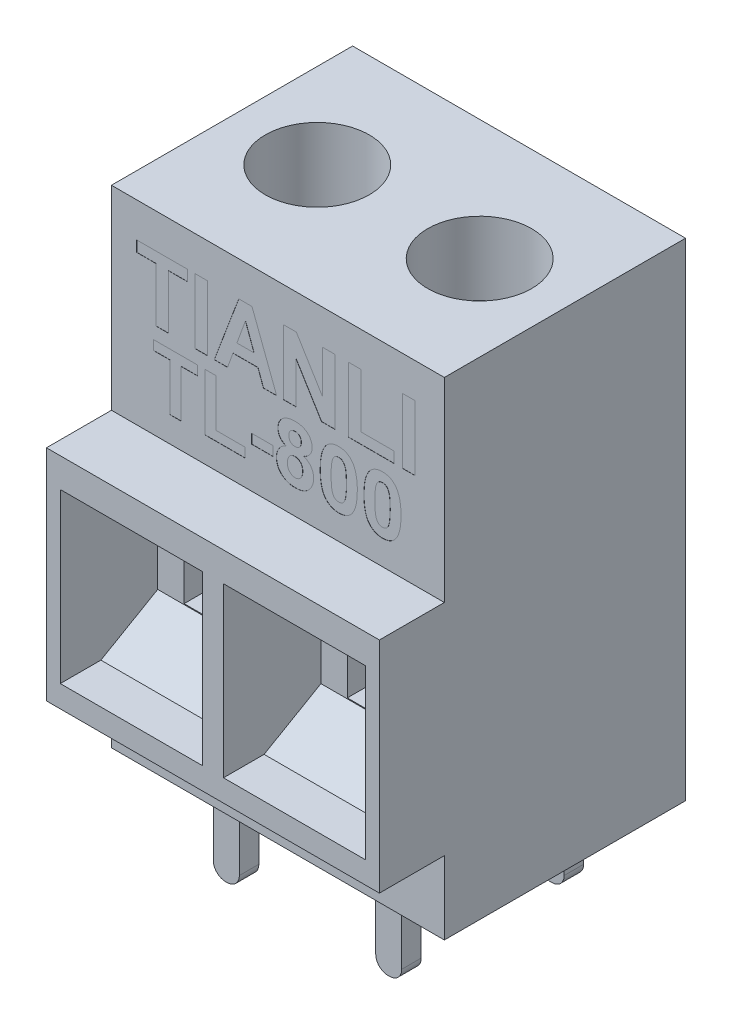
SolidWorks part; units mm, degrees
ref_plane "Front Plane" through (0, 0, 0) normal (0, 0, 1) x (1, 0, 0)
ref_plane "Top Plane" through (0, 0, 0) normal (0, 1, 0) x (1, 0, 0)
ref_plane "Right Plane" through (0, 0, 0) normal (1, 0, 0) x (0, 0, -1)
sketch "Sketch1" plane through (0, 0, 0) normal (1, 0, 0) x (0, 0, -1)
  line L0 (0, 66.3882) -> (0, -65.5147) construction
  line L1 (7.425, 15) -> (-7.425, 15)
  line L2 (-7.425, 15) -> (-7.425, 3)
  line L3 (-7.425, 3) -> (-11.425, 3)
  line L4 (-11.425, 3) -> (-11.425, -10.5)
  line L5 (-11.425, -10.5) -> (-7.425, -10.5)
  line L6 (-7.425, -10.5) -> (-7.425, -15)
  line L7 (-7.425, -15) -> (7.425, -15)
  line L8 (7.425, -15) -> (7.425, 15)
  point P5 (0, -65.5147)
  point P12 (0, 66.3882)
  point P13 (-6.1478, 3.3163)
  point P14 (-6.9448, -29.5223)
  point P15 (0, 15)
  point P16 (7.425, 0)
  dimension "D1" = 14.85
  dimension "D2" = 30
  dimension "D3" = 12
  dimension "D4" = 4
  dimension "D5" = 4.5
extrude "Boss-Extrude1" add sketch "Sketch1" along normal mid plane 20.5
sketch "Sketch2" plane through (0, 0, 11.425) normal (0, 0, 1) x (1, 0, 0)
  line L0 (0, 6.6704) -> (0, -3.1764) construction
  line L1 (9.4, -9.15) -> (0.65, -9.15)
  line L2 (-9.4, 1.2) -> (-0.65, 1.2)
  line L3 (-9.4, 1.2) -> (-9.4, -9.15)
  line L4 (-9.4, -9.15) -> (-0.65, -9.15)
  line L5 (-0.65, 1.2) -> (-0.65, -9.15)
  line L6 (-9.4, 1.2) -> (-0.65, -9.15) construction
  line L7 (-9.4, -9.15) -> (-0.65, 1.2) construction
  line L8 (0.65, 1.2) -> (0.65, -9.15)
  line L9 (9.4, 1.2) -> (0.65, 1.2)
  line L10 (9.4, 1.2) -> (9.4, -9.15)
  line L11 (10.25, -10.5) -> (-10.25, -10.5) construction
  point P3 (-5.025, -3.975)
  dimension "D1" = 8.75
  dimension "D2" = 10.35
  dimension "D3" = 1.35
  dimension "D4" = 1.3
extrude "Cut-Extrude1" cut sketch "Sketch2" against normal blind 6
sketch "Sketch4" plane through (0, 0, 5.425) normal (0, 0, 1) x (1, 0, 0)
  line L0 (-0.65, -9.15) -> (-0.65, 1.2) construction
  line L1 (-2.275, -0.875) -> (-7.775, -0.875)
  line L2 (-2.275, -0.875) -> (-2.275, -7.075)
  line L3 (-2.275, -7.075) -> (-7.775, -7.075)
  line L4 (-7.775, -0.875) -> (-7.775, -7.075)
  line L5 (-2.275, -0.875) -> (-7.775, -7.075) construction
  line L6 (-2.275, -7.075) -> (-7.775, -0.875) construction
  line L7 (-0.65, 1.2) -> (-9.4, 1.2) construction
  line L8 (0, 0) -> (0, 5.9557) construction
  line L9 (2.275, -7.075) -> (7.775, -7.075)
  line L10 (7.775, -0.875) -> (7.775, -7.075)
  line L11 (2.275, -0.875) -> (7.775, -0.875)
  line L12 (2.275, -0.875) -> (2.275, -7.075)
  point P0 (-5.025, -3.975)
  point P7 (-0.65, -3.975)
  point P10 (-5.025, 1.2)
  dimension "D1" = 6.2
  dimension "D2" = 5.5
extrude "Cut-Extrude2" cut sketch "Sketch4" against normal blind 6
chamfer "Chamfer1" distance 3.5 angle 30 4 edges at (5.025, -9.15, 5.425) (5.025, 1.2, 5.425) (-5.025, 1.2, 5.425) (-5.025, -9.15, 5.425)
sketch "Sketch5" plane through (0, 15, 0) normal (0, 1, 0) x (1, 0, 0)
  line L0 (0, 0) -> (-10.25, 0) construction
  line L1 (0, 0) -> (0, -7.425) construction
  line L2 (-10.25, 7.425) -> (-10.25, -7.425) construction
  line L3 (10.25, -7.425) -> (-10.25, -7.425) construction
  circle A0 centre (-5, 0) radius 3.2
  circle A1 centre (5, 0) radius 3.2
  dimension "D1" = 6.4
  dimension "D2" = 10
extrude "Cut-Extrude3" cut sketch "Sketch5" against normal blind 4.5
sketch "Sketch6" plane through (0, 10.5, 0) normal (0, 1, 0) x (1, 0, 0)
  line L0 (-7.2223, 0) -> (-2.7777, 0)
  line L1 (-5, -1.75) -> (-5, 1.75)
  line L2 (0, 0) -> (0, -2.7983) construction
  line L3 (5, -1.75) -> (5, 1.75)
  line L4 (7.2223, 0) -> (2.7777, 0)
  line L5 (-5, 3.2) -> (-5, -3.2) construction
  circle A2 centre (-5, 0) radius 3.2 construction
  circle A3 centre (-5, 0) radius 3.2 construction
  point P2 (-5, 3.2)
  point P3 (-5, 3.2)
  point P10 (-5, 0)
  dimension "D1" = 3.5
  dimension "D2" = 5
extrude "Cut-Extrude-Thin1" cut sketch "Sketch6" against normal blind 1.5 thin thin type mid plane wall 1
sketch "Sketch7" plane through (0, -15, 0) normal (0, -1, 0) x (1, 0, 0)
  line L0 (0, 14.2864) -> (0, -10.6744) construction
  line L1 (-13.0408, 0) -> (12.0493, 0) construction
  line L2 (-4.2, 4.4) -> (-5.8, 4.4)
  line L3 (4.2, 5.6) -> (5.8, 5.6)
  line L4 (4.2, 5.6) -> (4.2, 4.4)
  line L5 (4.2, 4.4) -> (5.8, 4.4)
  line L6 (5.8, 5.6) -> (5.8, 4.4)
  line L7 (4.2, 5.6) -> (5.8, 4.4) construction
  line L8 (4.2, 4.4) -> (5.8, 5.6) construction
  line L9 (-5.8, 5.6) -> (-5.8, 4.4)
  line L10 (-4.2, 5.6) -> (-5.8, 5.6)
  line L11 (-4.2, 5.6) -> (-4.2, 4.4)
  line L12 (-4.2, -5.6) -> (-4.2, -4.4)
  line L13 (-4.2, -5.6) -> (-5.8, -5.6)
  line L14 (-5.8, -5.6) -> (-5.8, -4.4)
  line L15 (-4.2, -4.4) -> (-5.8, -4.4)
  line L16 (4.2, -4.4) -> (5.8, -4.4)
  line L17 (5.8, -5.6) -> (5.8, -4.4)
  line L18 (4.2, -5.6) -> (5.8, -5.6)
  line L19 (4.2, -5.6) -> (4.2, -4.4)
  point P9 (5, 5)
  dimension "D1" = 10
  dimension "D2" = 10
  dimension "D3" = 1.6
  dimension "D4" = 1.2
extrude "Boss-Extrude2" add sketch "Sketch7" along normal blind 5.45
fillet "Fillet1" radius 0.75 8 edges at (4.2, -20.45, -5) (5.8, -20.45, -5) (-4.2, -20.45, -5) (-5.8, -20.45, -5) (-5.8, -20.45, 5) (-4.2, -20.45, 5) (4.2, -20.45, 5) (5.8, -20.45, 5)
sketch "Sketch8" plane through (0, 0, 7.425) normal (0, 0, 1) x (1, 0, 0)
  line L0 (-10.25, 8.8613) -> (10.25, 8.8613) construction
  line L1 (-10.25, 4.5647) -> (10.25, 4.5647) construction
  line L2 (10.25, 15) -> (10.25, 3) construction
  text T0 "TIANLI" font "Arial" height 4
  text T1 "TL-800" font "Arial" height 3.5
  point P4 (0, 8.8613)
  point P5 (0, 4.5647)
  point P7 (10.25, 4.5647)
  point P10 (10.25, 10.4645)
extrude "Cut-Extrude4" cut sketch "Sketch8" against normal blind 0.01
